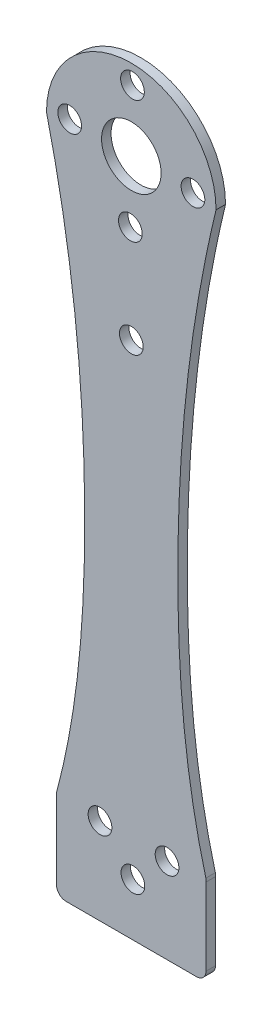
SolidWorks part; units mm, degrees
ref_plane "Front Plane" through (0, 0, 0) normal (0, 0, 1) x (1, 0, 0)
ref_plane "Top Plane" through (0, 0, 0) normal (0, 1, 0) x (1, 0, 0)
ref_plane "Right Plane" through (0, 0, 0) normal (1, 0, 0) x (0, 0, -1)
sketch "Sketch1" plane through (0, 0, 0) normal (0, 0, 1) x (1, 0, 0)
  line L0 (0, 18.0975) -> (0, -5.9817) construction
  line L1 (10.0076, 5.9817) -> (-10.0076, 5.9817) construction
  line L2 (10.0076, 5.6226) -> (10.0076, -4.7117)
  line L3 (8.7376, -5.9817) -> (-8.7376, -5.9817)
  line L4 (-10.0076, 5.6226) -> (-10.0076, -4.7117)
  line L5 (10.0076, 5.9817) -> (-9.5357, -5.6996) construction
  line L6 (9.5357, -5.6996) -> (-10.0076, 5.9817) construction
  line L7 (0, -5.9817) -> (72.9539, -5.9817) construction
  line L8 (0, -5.9817) -> (-97.5928, -5.9817) construction
  line L9 (0, 95.6183) -> (72.9539, 95.6183) construction
  line L10 (0, 95.6183) -> (-75.3737, 95.6183) construction
  line L11 (-7.5692, 18.0975) -> (0, 18.0975) construction
  line L12 (-6.2357, 38.3159) -> (0, 38.3159) construction
  line L13 (0, 63.4873) -> (7.6327, 63.4873) construction
  line L14 (7.6327, 63.4873) -> (0, 63.4873) construction
  line L15 (0, 63.4873) -> (-7.6327, 63.4873) construction
  line L16 (0, 38.3159) -> (6.2357, 38.3159) construction
  line L17 (0, 18.0975) -> (7.5692, 18.0975) construction
  line L18 (0, 18.0975) -> (0, 38.3159) construction
  line L19 (0, 38.3159) -> (0, 63.4873) construction
  line L20 (0, 63.4873) -> (0, 84.8233) construction
  line L21 (0, 84.8233) -> (-11.2522, 84.8233) construction
  line L22 (0, 84.8233) -> (11.2522, 84.8233) construction
  arc A0 (11.3538, 84.2645) -> (-11.3538, 84.2645) centre (0, 84.2645) ccw
  arc A1 (10.0076, -4.7117) -> (8.7376, -5.9817) centre (8.7376, -4.7117) cw
  arc A2 (-10.0076, -4.7117) -> (-8.7376, -5.9817) centre (-8.7376, -4.7117) ccw
  arc A3 (-9.9908, 6.0846) -> (-10.0076, 5.6226) centre (-3.6576, 5.6226) ccw
  arc A4 (9.9908, 6.0846) -> (10.0076, 5.6226) centre (3.6576, 5.6226) cw
  spline S0 degree 3 poles (9.9908, 6.0846) (7.1678, 16.5915) (5.0515, 42.9388) (7.718, 69.2245) (11.3538, 84.2645) knots 0 0 0 0 0.412468 1 1 1 1
  spline S1 degree 3 poles (-9.9908, 6.0846) (-7.1678, 16.5915) (-5.0515, 42.9388) (-7.718, 69.2245) (-11.3538, 84.2645) knots 0 0 0 0 0.412468 1 1 1 1
  point P0 (0, 0)
  dimension "D3" = 1.27
  dimension "D1" = 6.35
  dimension "D2" = 6.35
extrude "Boss-Extrude1" add sketch "Sketch1" along normal blind 1.27
sketch "Sketch3" plane through (0, 0, 1.27) normal (0, 0, 1) x (1, 0, 0)
  line L0 (0.0095, 18.0984) -> (0.0095, -5.9808) construction
  line L1 (10.0171, 5.9826) -> (-9.9981, 5.9826) construction
  line L5 (10.0171, 5.9826) -> (-9.5261, -5.6987) construction
  line L6 (9.5452, -5.6987) -> (-9.9981, 5.9826) construction
  line L7 (0.0095, -5.9808) -> (72.9634, -5.9808) construction
  line L8 (0.0095, -5.9808) -> (-97.5832, -5.9808) construction
  line L9 (0.0095, 95.6192) -> (72.9634, 95.6192) construction
  line L10 (0.0095, 95.6192) -> (-75.3641, 95.6192) construction
  line L11 (-7.5597, 18.0984) -> (0.0095, 18.0984) construction
  line L12 (-6.2262, 38.3168) -> (0.0095, 38.3168) construction
  line L14 (7.6422, 63.4882) -> (0.0095, 63.4882) construction
  line L15 (0.0095, 63.4882) -> (-7.6232, 63.4882) construction
  line L16 (0.0095, 38.3168) -> (6.2452, 38.3168) construction
  line L17 (0.0095, 18.0984) -> (7.5787, 18.0984) construction
  line L18 (0.0095, 18.0984) -> (0.0095, 38.3168) construction
  line L19 (0.0095, 38.3168) -> (0.0095, 63.4882) construction
  line L20 (0.0095, 63.4882) -> (0.0095, 84.8242) construction
  line L21 (0.0095, 84.8242) -> (-11.2427, 84.8242) construction
  line L22 (0.0095, 84.8242) -> (11.2617, 84.8242) construction
  circle A0 centre (0.0095, 63.4882) radius 1.5875
  circle A1 centre (-4.1879, 5.6239) radius 1.5875 construction
  circle A2 centre (4.7909, 5.46) radius 1.5875 construction
  circle A3 centre (0.2196, 1.0526) radius 1.5875 construction
  circle A4 centre (-4.1879, 5.6239) radius 1.5875
  circle A5 centre (0.0095, 84.8242) radius 3.9878
  circle A6 centre (4.7909, 5.46) radius 1.5875
  circle A7 centre (0.2196, 1.0526) radius 1.5875
  circle A8 centre (8.2634, 84.6858) radius 1.5875 construction
  circle A9 centre (-0.1171, 76.5315) radius 1.5875 construction
  circle A10 centre (-8.2439, 84.9871) radius 1.5875 construction
  circle A11 centre (0.1609, 93.1164) radius 1.5875 construction
  circle A12 centre (8.2634, 84.6858) radius 1.5875
  circle A13 centre (-0.1171, 76.5315) radius 1.5875
  circle A14 centre (-8.2439, 84.9871) radius 1.5875
  circle A15 centre (0.1609, 93.1164) radius 1.5875
  point P0 (0.0095, 0.0009)
  dimension "D1" = 3.175
extrude "Cut-Extrude1" cut sketch "Sketch3" against normal through all
equation "\"HOLE SIZE\"= .125"
